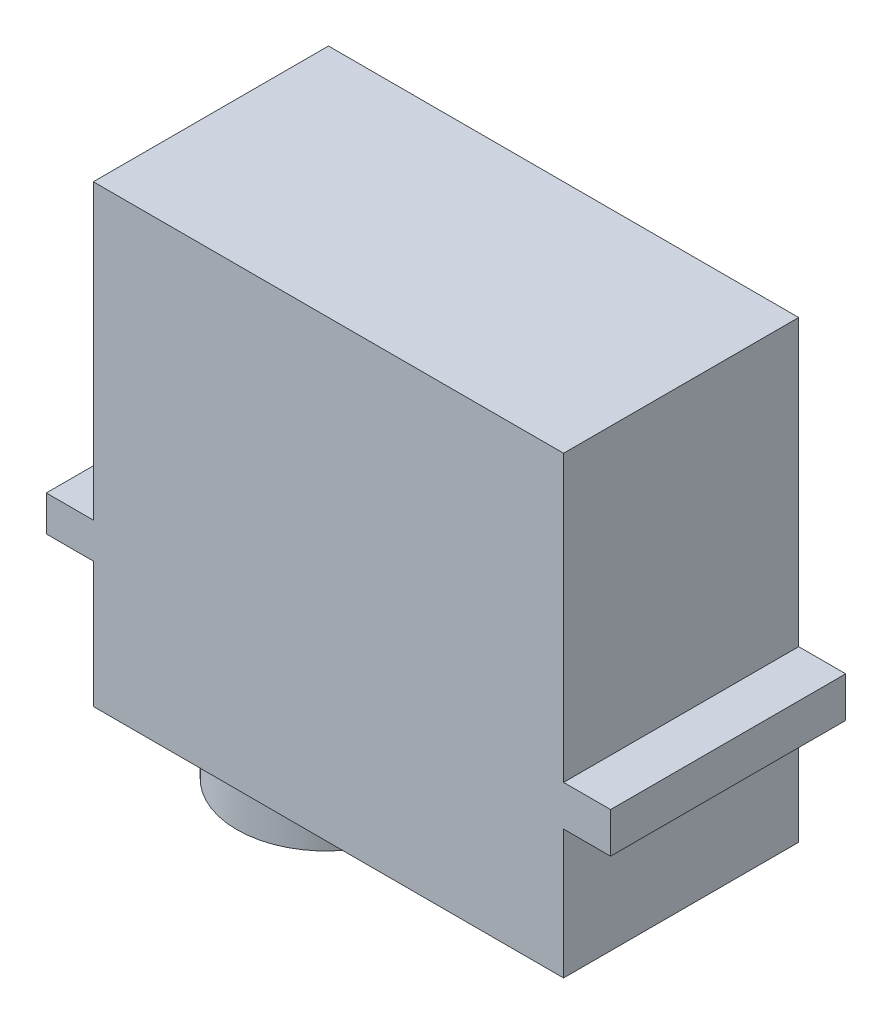
SolidWorks part; units mm, degrees
ref_plane "前视基准面" through (0, 0, 0) normal (0, 0, 1) x (1, 0, 0)
ref_plane "上视基准面" through (0, 0, 0) normal (0, 1, 0) x (1, 0, 0)
ref_plane "右视基准面" through (0, 0, 0) normal (1, 0, 0) x (0, 0, -1)
other "Configuration Table"
sketch "草图3" plane through (0, 0, 0) normal (0, 0, 1) x (1, 0, 0)
  line L1 (0, 0) -> (40, 0)
  line L2 (0, 0) -> (0, 38.6565)
  line L3 (0, 38.6565) -> (40, 38.6565)
  line L4 (40, 0) -> (40, 38.6565)
extrude "凸台-拉伸1" add sketch "草图3" along normal blind 20
sketch "草图4" plane through (0, 0, 0) normal (0, 1, 0) x (1, 0, 0)
  circle A2 centre (9.185, -9.4007) radius 7.5716
extrude "凸台-拉伸2" add sketch "草图4" against normal blind 6 contours A2
sketch "草图5" plane through (0, 0, 0) normal (-1, 0, 0) x (0, 0, 1)
  line L0 (0, 38.6565) -> (0, 0) construction
  line L1 (0, 13.7308) -> (20, 13.7308)
  line L2 (0, 13.7308) -> (0, 10.7104)
  line L3 (0, 10.7104) -> (20, 10.7104)
  line L4 (20, 13.7308) -> (20, 10.7104)
  line L5 (20, 38.6565) -> (20, 0) construction
extrude "凸台-拉伸3" add sketch "草图5" along normal blind 4.0022 contours L1 L4 L3 L2
sketch "草图6" plane through (40, 0, 0) normal (1, 0, 0) x (0, 0, -1)
  line L0 (-20, 0) -> (-20, 38.6565) construction
  line L5 (-20, 14.4092) -> (0, 14.4092)
  line L6 (-20, 14.4092) -> (-20, 10.9736)
  line L7 (-20, 10.9736) -> (0, 10.9736)
  line L8 (0, 14.4092) -> (0, 10.9736)
  line L9 (0, 0) -> (0, 38.6565) construction
extrude "凸台-拉伸4" add sketch "草图6" along normal blind 4
ref_plane "基准面1" through (-4.0022, 10.7104, 0) normal (0, -1, 0) x (-1, 0, 0)
